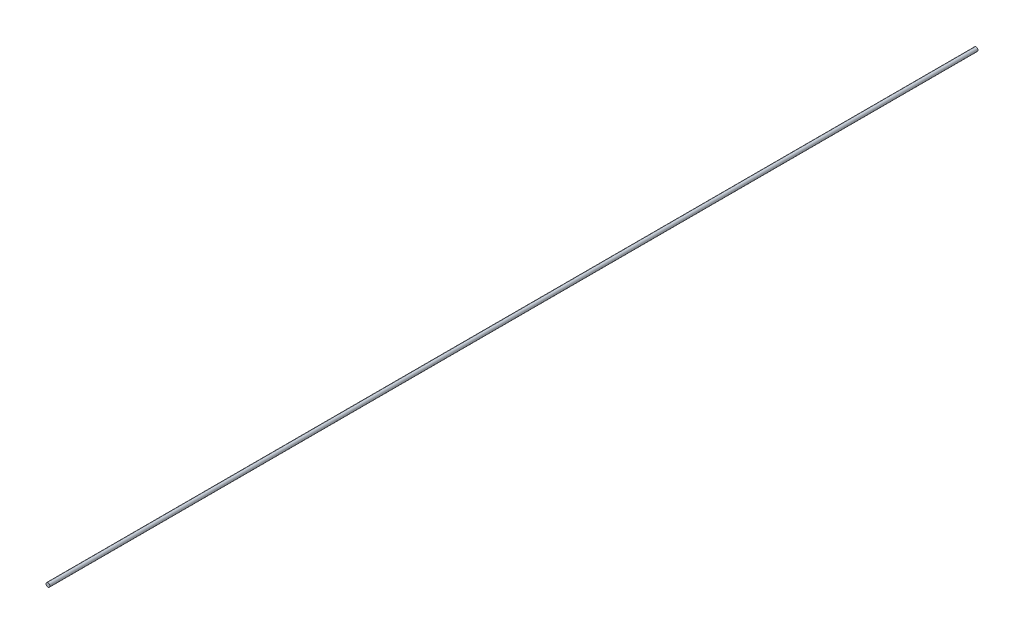
SolidWorks part; units mm, degrees
material "Hexcel AS4C (3000 Filaments)"
ref_plane "Front Plane" through (0, 0, 0) normal (0, 0, 1) x (1, 0, 0)
ref_plane "Top Plane" through (0, 0, 0) normal (0, 1, 0) x (1, 0, 0)
ref_plane "Right Plane" through (0, 0, 0) normal (1, 0, 0) x (0, 0, -1)
sketch "Sketch1" plane through (0, 0, 0) normal (0, 0, 1) x (1, 0, 0)
  circle A1 centre (-44.7215, -1.872) radius 1.5875
  dimension "D1" = 3.175
extrude "Boss-Extrude1" add sketch "Sketch1" against normal up to surface (761.9997 mm away)
